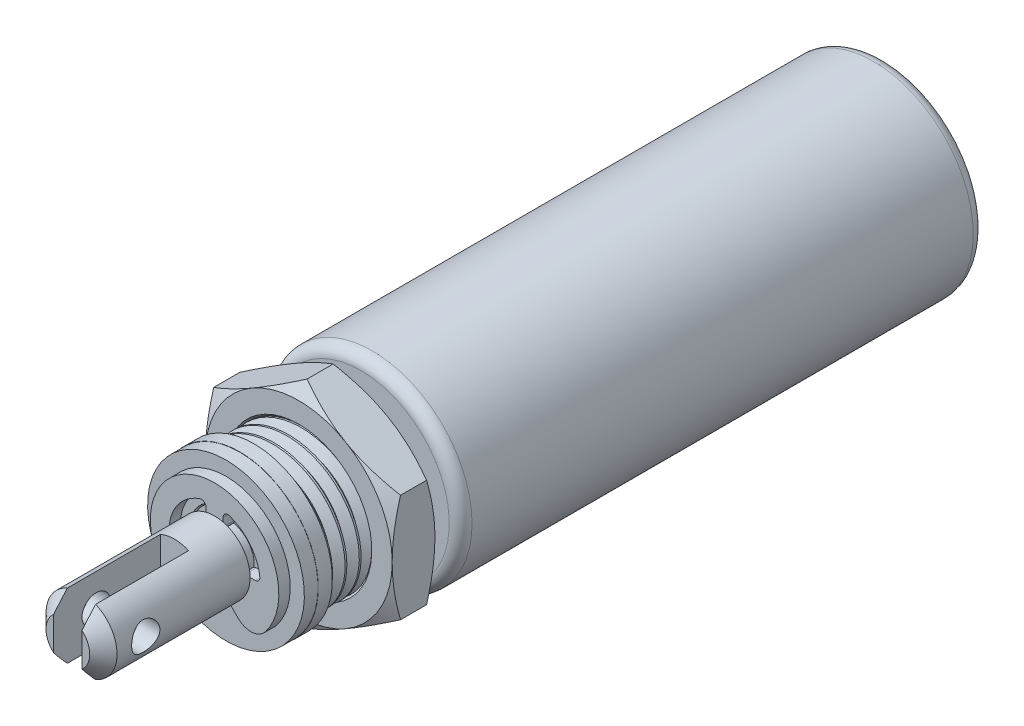
SolidWorks part; units mm, degrees
ref_plane "Front Plane" through (0, 0, 0) normal (0, 0, 1) x (1, 0, 0)
ref_plane "Top Plane" through (0, 0, 0) normal (0, 1, 0) x (1, 0, 0)
ref_plane "Right Plane" through (0, 0, 0) normal (1, 0, 0) x (0, 0, -1)
sketch "Sketch0" plane through (0, 0, 0) normal (1, 0, 0) x (0, 0, -1)
  line L0 (0, 0) -> (29.21, 0) construction
  line L1 (0, 0) -> (-16.3322, 0) construction
  line L2 (29.21, 5.5626) -> (29.21, -5.5626) construction
  line L3 (0, 3.9688) -> (0, -3.9688) construction
  line L4 (-16.3322, 1.9812) -> (-16.3322, -1.9812) construction
  line L5 (-16.3322, 0) -> (-22.6822, 0) construction
  point P10 (-13.97, 0)
  point P12 (-5.842, 0)
  dimension "D1" = 13.97
  dimension "Lg." = 29.21
  dimension "Dia." = 11.1252
  dimension "Rod Dia." = 3.9624
  dimension "A" = 16.3322
  dimension "Thread OD" = 7.9375
  dimension "Stroke" = 6.35
  dimension "D2" = 2.3622
  dimension "D3" = 5.842
sketch "Sketch1" plane through (0, 0, 0) normal (1, 0, 0) x (0, 0, -1)
  line L0 (29.21, 0) -> (0, 0) construction
  line L1 (28.575, 5.5626) -> (0.635, 5.5626)
  line L3 (29.21, 0) -> (0, 0)
  line L5 (29.21, 0) -> (29.21, 4.9276)
  line L9 (0, 4.9276) -> (0, 0)
  arc A1 (29.21, 4.9276) -> (28.575, 5.5626) centre (28.575, 4.9276) ccw
  arc A2 (0, 4.9276) -> (0.635, 5.5626) centre (0.635, 4.9276) cw
  dimension "D1" = 0.635
revolve "Revolve1" add sketch "Sketch1" angle 360 mid plane about L0
sketch "Sketch2" plane through (0, 0, 0) normal (1, 0, 0) x (0, 0, -1)
  line L0 (0, 0) -> (-16.3322, 0) construction
  line L3 (-5.842, 2.2987) -> (-5.842, 3.6513)
  line L4 (-5.842, 3.6513) -> (-5.5245, 3.9688)
  line L5 (-5.5245, 3.9688) -> (-1.0796, 3.9688)
  line L6 (-1.0796, 3.9688) -> (-0.635, 3.3337)
  line L7 (-0.635, 3.3337) -> (0, 3.3337)
  line L8 (0, 3.3337) -> (0, 1.9812)
  line L9 (-5.5245, 1.9812) -> (0, 1.9812)
  line L11 (-5.5245, 1.9812) -> (-5.842, 2.2987)
  dimension "D1" = 0.635
  dimension "D4" = 0.3175
  dimension "D5" = 5.842
  dimension "D2" = 55
  dimension "D6" = 0.635
  dimension "D3" = 45
  dimension "D8" = 0.3175
  dimension "D7" = 45
revolve "Revolve2" add sketch "Sketch2" angle 360 mid plane about L0
sketch "Sketch3" plane through (0, 0, 0) normal (1, 0, 0) x (0, 0, -1)
  line L0 (-16.3322, 0) -> (0, 0) construction
  line L1 (-15.5702, 1.9812) -> (-16.3322, 1.2192)
  line L2 (0, 0) -> (-16.3322, 0)
  line L3 (0, 0) -> (0, 1.9812)
  line L4 (0, 1.9812) -> (-7.4168, 1.9812)
  line L5 (-16.3322, 0) -> (-16.3322, 1.2192)
  line L6 (-15.5702, 1.9812) -> (-16.3322, 1.9812) construction
  line L7 (-16.3322, 1.9812) -> (-16.3322, 1.2192) construction
  line L8 (-8.1534, 1.9812) -> (-8.1534, 1.4732)
  line L9 (-8.1534, 1.4732) -> (-7.4168, 1.4732)
  line L10 (-7.4168, 1.4732) -> (-7.4168, 1.9812)
  line L11 (-8.1534, 1.9812) -> (-15.5702, 1.9812)
  dimension "D1" = 0.762
  dimension "D2" = 0.508
  dimension "D3" = 0.7366
  dimension "D4" = 8.1788
revolve "Revolve3" add sketch "Sketch3" angle 360 mid plane about L2
sketch "Sketch4" plane through (0, 0, 0) normal (0, 1, 0) x (0, 0, -1)
  line L1 (-16.3322, 0.7874) -> (-10.3886, 0.7874)
  line L2 (-16.3322, 0.7874) -> (-16.3322, -0.7874)
  line L3 (-16.3322, -0.7874) -> (-10.3886, -0.7874)
  line L4 (-10.3886, 0.7874) -> (-10.3886, -0.7874)
  dimension "D1" = 1.5748
  dimension "D2" = 5.9436
extrude "Cut-Extrude1" cut sketch "Sketch4" against normal up to surface and the other way up to surface up to face at (0, 1.9812, 7.4168) other way up to face at (0, 1.9812, 7.4168)
sketch "Sketch5" plane through (0, 0, 0) normal (1, 0, 0) x (0, -1, 0)
  line L0 (0, -16.3322) -> (0, -13.97) construction
  circle A0 centre (0, -13.97) radius 0.7874
  dimension "D1" = 1.5748
extrude "Cut-Extrude2" cut sketch "Sketch5" along normal up to surface and the other way up to surface up to face at (0, 1.9812, 7.4168) other way up to face at (0, 1.9812, 7.4168)
sketch "Sketch8" plane through (0, 0, 8.1534) normal (0, 0, 1) x (1, 0, 0)
  line L0 (-0.4762, 2.1662) -> (-0.4763, 1.6872)
  line L1 (0.4762, 2.1662) -> (0.4762, 1.6872)
  line L2 (-1.3076, -2.2922) -> (-0.6697, -1.6543)
  line L3 (1.3076, -2.2922) -> (0.6697, -1.6543)
  line L4 (0, 1.4478) -> (0, 0) construction
  line L5 (-2.2718, 0) -> (-1.6827, 0)
  line L6 (1.6827, 0) -> (2.2718, 0)
  line L7 (0, 1.4478) -> (0, 3.5814) construction
  circle A0 centre (0, 0) radius 1.4478 construction
  circle A1 centre (0, 0) radius 3.5814 construction
  circle A2 centre (0, 0) radius 2.54 construction
  arc A3 (-2.8283, -2.197) -> (2.8283, -2.197) centre (0, 0) cw
  arc A4 (-2.5243, 0.2822) -> (-0.8114, 2.4069) centre (0, 0) cw
  arc A5 (0.8114, 2.4069) -> (2.5243, 0.2822) centre (0, 0) cw
  arc A6 (-0.1891, 1.4354) -> (0.1891, 1.4354) centre (0, 0) cw
  arc A7 (-0.8114, 2.4069) -> (-0.4762, 2.1662) centre (-0.7303, 2.1662) cw
  arc A8 (-0.1891, 1.4354) -> (-0.4763, 1.6872) centre (-0.2223, 1.6872) cw
  arc A9 (0.1891, 1.4354) -> (0.4762, 1.6872) centre (0.2222, 1.6872) ccw
  arc A10 (0.8114, 2.4069) -> (0.4762, 2.1662) centre (0.7302, 2.1662) ccw
  arc A11 (-1.4316, -0.2161) -> (-0.7225, -1.2546) centre (0, 0) ccw
  arc A12 (1.4316, -0.2161) -> (0.7225, -1.2546) centre (0, 0) cw
  arc A13 (2.5243, 0.2822) -> (2.2718, 0) centre (2.2718, 0.254) cw
  arc A14 (0.7225, -1.2546) -> (0.6697, -1.6543) centre (0.8493, -1.4747) ccw
  arc A15 (1.6827, 0) -> (1.4316, -0.2161) centre (1.6827, -0.254) ccw
  arc A16 (-2.2718, 0) -> (-2.5243, 0.2822) centre (-2.2718, 0.254) cw
  arc A17 (-1.6827, 0) -> (-1.4316, -0.2161) centre (-1.6827, -0.254) cw
  arc A18 (-0.7225, -1.2546) -> (-0.6697, -1.6543) centre (-0.8493, -1.4747) cw
  arc A19 (-2.8283, -2.197) -> (-1.3076, -2.2922) centre (-2.026, -1.5738) ccw
  arc A20 (2.8283, -2.197) -> (1.3076, -2.2922) centre (2.026, -1.5738) cw
  point P18 (-0.4763, 1.3672)
  point P23 (0.4762, 2.495)
  point P31 (2.54, 0)
  point P35 (1.4478, 0)
  point P38 (-2.54, 0)
  point P41 (-1.4478, 0)
  point P44 (-0.4053, -1.3899)
  point P47 (-1.9918, -2.9764)
  dimension "D1" = 2.8956
  dimension "D2" = 7.1628
  dimension "D3" = 5.08
  dimension "D5" = 0.254
  dimension "D6" = 1.016
  dimension "D8" = 1.1906
  dimension "D4" = 0.9525
  dimension "D7" = 45
extrude "Boss-Extrude1" add sketch "Sketch8" against normal blind 0.635 separate body
sketch "Sketch9" plane through (0, 0, 0) normal (1, 0, 0) x (0, 0, -1)
  line L1 (-7.5184, 4.3688) -> (-6.7564, 4.3688)
  line L2 (-7.5184, 4.3688) -> (-7.5184, 2.051)
  line L3 (-7.5184, 2.051) -> (-6.7564, 2.051)
  line L4 (-6.7564, 4.3688) -> (-6.7564, 2.051)
  line L5 (0, 0) -> (-16.3322, 0) construction
  line L6 (-7.5184, -2.197) -> (-7.5184, 3.5814) construction
  line L7 (-16.3322, 0.9308) -> (-16.3322, -0.9308) construction
  dimension "D1" = 8.7376
  dimension "D2" = 4.1021
  dimension "D3" = 0.762
revolve "Revolve4" add sketch "Sketch9" angle 360 about L5
sketch "Sketch10" plane through (0, 0, 0) normal (1, 0, 0) x (0, 0, -1)
  line L0 (0, 0) -> (-16.3322, 0) construction
  line L1 (-6.7564, 4.3815) -> (-5.969, 4.3815)
  line L2 (-6.7564, 4.3815) -> (-6.7564, 1.8669)
  line L3 (-6.7564, 1.8669) -> (-5.969, 1.8669)
  line L4 (-5.969, 4.3815) -> (-5.969, 1.8669)
  line L5 (-16.3322, 0.9308) -> (-16.3322, -0.9308) construction
  line L6 (-6.7564, -4.3688) -> (-6.7564, 4.3688) construction
  dimension "D1" = 8.763
  dimension "D2" = 3.7338
  dimension "D3" = 0.7874
revolve "Revolve5" add sketch "Sketch10" angle 360 about L0
move or copy body "Body-Move/Copy1" bodies to move or copy 107 114 113 115 copy yes number of copies 1 translate (0, 0, 6.35)
sketch "SketchX" plane through (0, 0, 0) normal (1, 0, 0) x (0, 0, -1)
  line L1 (-22.6822, 0.9308) -> (-22.6822, -0.9308) construction
  line L3 (-21.9202, 1.818) -> (-16.7386, 1.818) construction
  line L4 (-21.9202, -1.818) -> (-16.7386, -1.818) construction
  line L5 (-16.7386, -1.818) -> (-16.7386, -1.9812) construction
  line L6 (-16.7386, -1.9812) -> (-14.5034, -1.9812) construction
  line L9 (-14.5034, 1.9812) -> (-16.7386, 1.9812) construction
  line L10 (-16.7386, 1.9812) -> (-16.7386, 1.818) construction
  line L12 (-12.319, -4.3815) -> (-12.319, 4.3815) construction
  line L13 (-21.9202, 1.818) -> (-16.7386, 1.818)
  line L14 (-22.6822, 0.9308) -> (-22.6822, -0.9308)
  line L15 (-21.9202, -1.818) -> (-16.7386, -1.818)
  line L16 (-16.7386, -1.818) -> (-16.7386, -1.9812)
  line L17 (-16.7386, -1.9812) -> (-14.5034, -1.9812)
  line L18 (-10.3886, 1.9812) -> (-12.319, 1.9812)
  line L19 (-16.7386, 1.9812) -> (-16.7386, 1.818)
  line L21 (-6.35, 1.9812) -> (-13.7668, 1.9812) construction
  line L22 (-10.3886, 1.9812) -> (-10.3886, 1.818) construction
  line L23 (-14.5034, 3.5814) -> (-14.5034, -2.197) construction
  line L24 (-13.8684, 3.5814) -> (-14.5034, 3.5814) construction
  line L25 (-13.8684, 4.3688) -> (-13.8684, -4.3688) construction
  line L26 (-13.1064, 4.3688) -> (-13.8684, 4.3688) construction
  line L27 (-12.319, -4.3815) -> (-12.319, -1.9812)
  line L28 (-12.319, -1.9812) -> (-10.3886, -1.9812)
  line L29 (-14.5034, -1.9812) -> (-14.5034, -2.5898)
  line L30 (-14.5034, 1.9812) -> (-16.7386, 1.9812)
  line L31 (-13.1064, 4.3815) -> (-13.1064, -4.3815) construction
  line L32 (-12.319, 4.3815) -> (-13.1064, 4.3815) construction
  line L33 (-14.5034, 3.5814) -> (-14.5034, 1.9812)
  line L34 (-13.8684, 3.5814) -> (-14.5034, 3.5814)
  line L35 (-13.8684, 4.3688) -> (-13.8684, 3.5814)
  line L36 (-13.1064, 4.3688) -> (-13.8684, 4.3688)
  line L37 (-13.1064, 4.3815) -> (-13.1064, 4.3688)
  line L38 (-12.319, 4.3815) -> (-13.1064, 4.3815)
  line L39 (-12.319, -4.3815) -> (-12.319, -1.9812)
  line L40 (-13.8684, -4.3688) -> (-13.1064, -4.3688) construction
  line L41 (-13.1064, -4.3815) -> (-12.319, -4.3815) construction
  line L42 (-13.8684, -4.3688) -> (-13.1064, -4.3688)
  line L43 (-13.1064, -4.3815) -> (-12.319, -4.3815)
  line L45 (-13.8684, -2.5898) -> (-13.8684, -4.3688)
  line L46 (-14.5034, -2.5898) -> (-13.8684, -2.5898) construction
  line L47 (-14.5034, -2.5898) -> (-13.8684, -2.5898)
  line L48 (-13.1064, -4.3688) -> (-13.1064, -4.3815)
  line L49 (-12.319, 1.9812) -> (-12.319, 4.3815)
  line L50 (-14.5034, -1.9812) -> (-14.5034, -2.5898)
  circle A0 centre (-20.32, 0) radius 0.7874 construction
  circle A4 centre (-20.32, 0) radius 0.7874
  spline S0 degree 3 poles (-1481.1325, -1369.2417) (1480.6854, 1318.4056) (-1524.3616, -1322.2286) (1437.4729, 1365.4337) knots -41.067597 -41.067597 -41.067597 -41.067597 40.854879 40.854879 40.854879 40.854879 only from (-21.9202, -1.818) to (-22.6822, -0.9308) construction
  spline S1 degree 3 poles (1501.9363, -1293.1466) (-1589.022, 1249.72) (1545.3459, -1245.8837) (-1545.5674, 1296.9463) knots -39.980575 -39.980575 -39.980575 -39.980575 42.202134 42.202134 42.202134 42.202134 only from (-22.6822, 0.9308) to (-21.9202, 1.818) construction
  spline S2 degree 3 poles (-21.9202, -1.818) (-22.1837, -1.5308) (-22.445, -1.2415) (-22.6822, -0.9308) knots 0 0 0 0 1 1 1 1
  spline S3 degree 3 poles (-22.6822, 0.9308) (-22.4456, 1.2407) (-22.1842, 1.5303) (-21.9202, 1.818) knots 0 0 0 0 1 1 1 1
delete or keep bodies "Body-Delete1" type delete bodies bodies 108 116 117 118
sketch "Sketch11" plane through (0, 0, 0) normal (0, 0, 1) x (1, 0, 0)
  line L1 (5.207, 3.0063) -> (0, 6.0125)
  line L2 (0, 6.0125) -> (-5.207, 3.0063)
  line L3 (-5.207, 3.0063) -> (-5.207, -3.0063)
  line L4 (-5.207, -3.0063) -> (0, -6.0125)
  line L5 (0, -6.0125) -> (5.207, -3.0063)
  line L6 (5.207, -3.0063) -> (5.207, 3.0063)
  circle A0 centre (0, 0) radius 5.207 construction
  circle A1 centre (0, 0) radius 3.9688
  circle A3 centre (0, 0) radius 3.9688 construction
  circle M4 centre (0, 0) radius 4.9276
  dimension "D1" = 10.414
extrude "Boss-Extrude2" add sketch "Sketch11" along normal blind 2.3813 from vertex at 1.0796 separate body contours A1 M4 | L5 L6 L1 L2 L3 L4 M4 starting at point (0, 3.9688, 1.0796)
sketch "Sketch12" plane through (0, 0, 0) normal (1, 0, 0) x (0, 0, -1)
  line L0 (0, 0) -> (-16.3322, 0) construction
  line L1 (-1.0796, 5.207) -> (-1.5447, 6.0125)
  line L2 (-3.4609, 6.0125) -> (-1.0796, 6.0125) construction
  line L3 (-1.5447, 6.0125) -> (-1.0796, 6.0125)
  line L4 (-1.0796, 6.0125) -> (-1.0796, 5.207)
  line L5 (-3.4609, 5.207) -> (-3.4609, 6.0125)
  line L6 (-3.4609, 5.207) -> (-2.9958, 6.0125)
  line L7 (-2.9958, 6.0125) -> (-3.4609, 6.0125)
  line L9 (-1.0796, 5.207) -> (0, 5.207) construction
  line L12 (-3.4609, 3.9688) -> (-3.4609, 4.0704)
  line L13 (-3.4609, 3.0063) -> (-3.4609, 6.0125) construction
  line L14 (-3.4609, 4.0704) -> (-3.3593, 3.9688)
  line L15 (-5.5245, 3.9688) -> (-1.0796, 3.9688) construction
  line L16 (-3.3593, 3.9688) -> (-3.4609, 3.9688)
  line L17 (-1.0796, 4.0704) -> (-1.1812, 3.9688)
  line L18 (-1.0796, 3.0063) -> (-1.0796, 6.0125) construction
  line L19 (-1.1812, 3.9688) -> (-1.0796, 3.9688)
  line L20 (-1.0796, 3.9688) -> (-1.0796, 4.0704)
  dimension "D1" = 30
  dimension "D2" = 0.1016
revolve "Cut-Revolve1" cut sketch "Sketch12" angle 360 about L0
sketch "Sketch6" plane through (0, 0, 5.842) normal (0, 0, 1) x (1, 0, 0)
  circle A1 centre (0, 0) radius 3.9688
  point P1 (0, 3.9688)
curve "Helix/Spiral1" pitch 0.7937 height 5.6832 turns 7.16 parameters "Pitch"=0.7937
sketch "Sketch7" plane through (0, 0, 0) normal (1, 0, 0) x (0, 0, -1)
  line L0 (-6.5861, 4.0547) -> (-5.7924, 4.0547) construction
  line L1 (-5.7924, 4.0547) -> (-6.1893, 3.3673) construction
  line L2 (-6.1893, 3.3673) -> (-6.5861, 4.0547) construction
  line L3 (-6.2389, 3.4532) -> (-6.1397, 3.4532) construction
  line L4 (-6.5365, 3.9688) -> (-5.842, 3.9688) construction
  line L5 (-6.1893, 3.3673) -> (-6.1893, 3.4532) construction
  line L6 (-6.1893, 3.9688) -> (-6.1893, 4.0547) construction
  line L7 (-6.2389, 3.4532) -> (-6.1397, 3.4532)
  line L8 (-6.1397, 3.4532) -> (-5.8172, 4.0117)
  line L9 (-5.8172, 4.0117) -> (-6.5613, 4.0117)
  line L10 (-6.5613, 4.0117) -> (-6.2389, 3.4532)
  line L11 (-6.1893, 3.3673) -> (-6.1893, -3.9688) construction
  line L12 (-6.1893, -3.9688) -> (-5.3955, -3.9688) construction
  line L13 (-5.3955, -3.9688) -> (-4.6018, -3.9688) construction
  line L14 (-4.6018, -3.9688) -> (-3.808, -3.9688) construction
  line L15 (-5.5245, -3.9688) -> (-1.0796, -3.9688) construction
  point P15 (-6.1893, 4.0117)
  dimension "D1" = 0.7937
  dimension "D2" = 0.0992
sweep "Cut-Sweep1" cut profiles "Sketch7" path "Helix/Spiral1"
equation "\"D3@Helix/Spiral1\" = \"Pitch@Helix/Spiral1\" + \"D5@Sketch2\" - ( \"D1@Sketch2\" * 1.5 ) "
equation "\"D1@Sketch7\" = \"Pitch@Helix/Spiral1\""
equation "\"D2@Sketch7\" = \"D1@Sketch7\" / 8"
